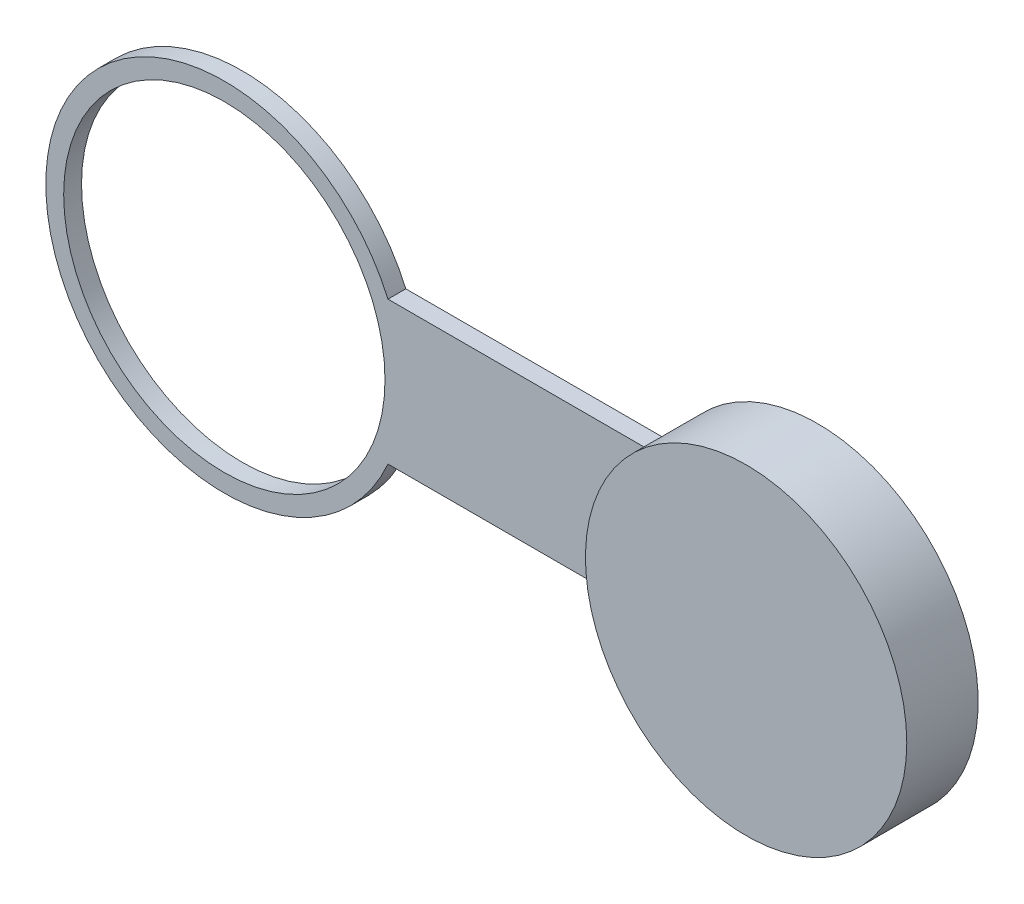
SolidWorks part; units mm, degrees
ref_plane "Front Plane" through (0, 0, 0) normal (0, 0, 1) x (1, 0, 0)
ref_plane "Top Plane" through (0, 0, 0) normal (0, 1, 0) x (1, 0, 0)
ref_plane "Right Plane" through (0, 0, 0) normal (1, 0, 0) x (0, 0, -1)
sketch "Sketch1" plane through (0, 0, 0) normal (0, 0, 1) x (1, 0, 0)
  circle A0 centre (0, 0) radius 45
  dimension "D1" = 90
extrude "Boss-Extrude1" add sketch "Sketch1" along normal blind 20 contours A0
sketch "Sketch2" plane through (0, 0, 0) normal (0, 0, -1) x (-1, 0, 0)
  line L0 (0, 0) -> (0, 20)
  line L1 (0, 0) -> (0, -20)
  line L2 (0, 20) -> (40.3113, 20)
  line L3 (0, -20) -> (40.3113, -20)
  line L4 (40.3113, -20) -> (115.3113, -20)
  line L5 (40.3113, 20) -> (115.3113, 20)
  circle A0 centre (0, 0) radius 45 construction
  arc A1 (40.3113, 20) -> (40.3113, -20) centre (0, 0) cw
  circle A2 centre (161.137, 0) radius 50
  circle A3 centre (161.137, 0) radius 45
  circle M11 centre (0, 0) radius 45
  dimension "D3" = 100
  dimension "D4" = 90
  dimension "D1" = 20
  dimension "D2" = 20
  dimension "D5" = 75
  dimension "D6" = 75
extrude "Boss-Extrude2" add sketch "Sketch2" against normal blind 5 contours A2 L5 L4 M11 | A2 A3
